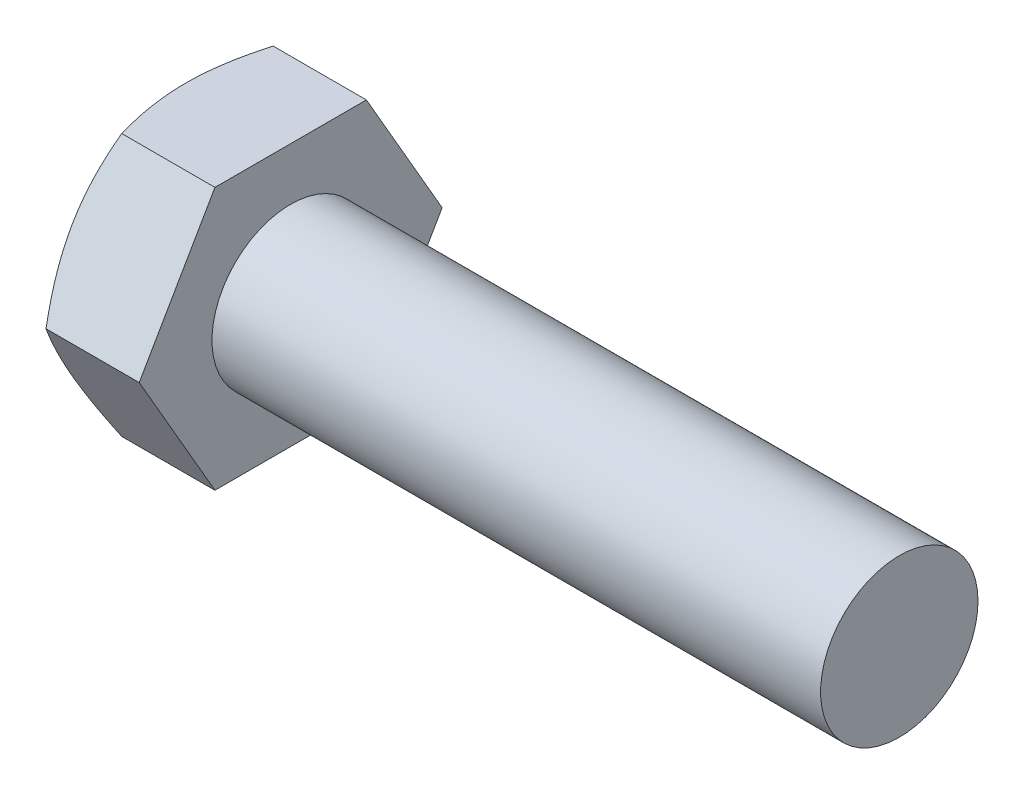
SolidWorks part; units mm, degrees
ref_plane "Front Plane" through (0, 0, 0) normal (0, 0, 1) x (1, 0, 0)
ref_plane "Top Plane" through (0, 0, 0) normal (0, 1, 0) x (1, 0, 0)
ref_plane "Right Plane" through (0, 0, 0) normal (1, 0, 0) x (0, 0, -1)
sketch "Sketch2" plane through (0, 0, 0) normal (1, 0, 0) x (0, 0, -1)
  circle A0 centre (0, 0) radius 3
  dimension "D1" = 6
extrude "Boss-Extrude1" add sketch "Sketch2" along normal blind 23.2
cosmetic thread "Cosmetic Thread1" parameters "D1"=6, "D2"=4.891
sketch "Sketch3" plane through (0, 0, 0) normal (-1, 0, 0) x (0, 0, 1)
  line L1 (5.7735, 0) -> (2.8868, 5)
  line L2 (2.8868, 5) -> (-2.8868, 5)
  line L3 (-2.8868, 5) -> (-5.7735, 0)
  line L4 (-5.7735, 0) -> (-2.8868, -5)
  line L5 (-2.8868, -5) -> (2.8868, -5)
  line L6 (2.8868, -5) -> (5.7735, 0)
  circle A0 centre (0, 0) radius 5 construction
  dimension "D1" = 10
extrude "Boss-Extrude2" add sketch "Sketch3" along normal blind 4
sketch "Sketch5" plane through (0, 0, 0) normal (0, 1, 0) x (1, 0, 0)
  line L0 (-4, 5) -> (-4, -5) construction
  line L1 (-4, -2.8868) -> (-4, 2.8868) construction
  line L2 (-4, 5) -> (-4, 5.7735)
  line L3 (-4, 5.7735) -> (-3.5534, 5.7735)
  line L4 (-4, 5.7735) -> (0, 5.7735) construction
  line L5 (-3.5534, 5.7735) -> (-4, 5)
  dimension "D1" = 10
  dimension "D2" = 5
  dimension "D3" = 30
revolve "Cut-Revolve1" cut sketch "Sketch5" angle 360 about axis through (23.2, 0, 0) along (-1, 0, 0)
